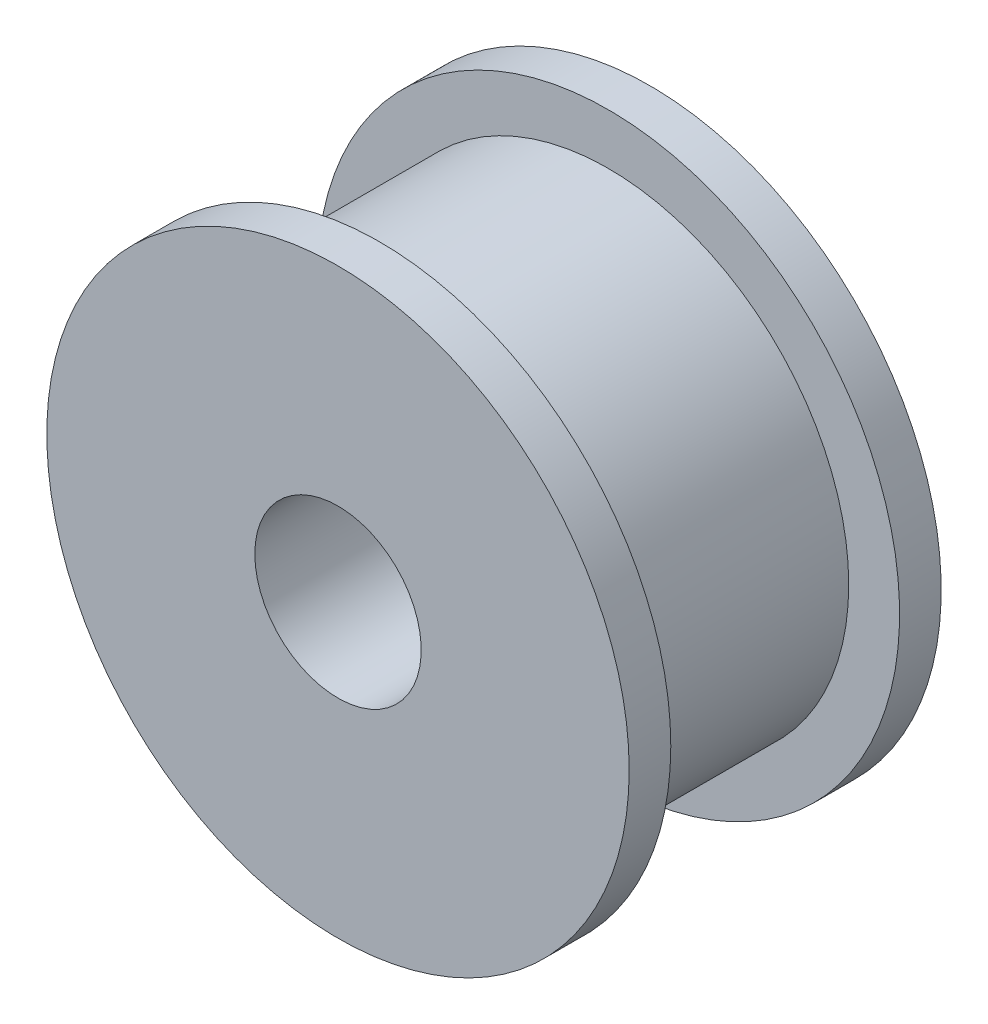
SolidWorks part; units mm, degrees
ref_plane "前视基准面" through (0, 0, 0) normal (0, 0, 1) x (1, 0, 0)
ref_plane "上视基准面" through (0, 0, 0) normal (0, 1, 0) x (1, 0, 0)
ref_plane "右视基准面" through (0, 0, 0) normal (1, 0, 0) x (0, 0, -1)
other "Configuration Table"
sketch "草图1" plane through (0, 0, 0) normal (0, 0, 1) x (1, 0, 0)
  circle A0 centre (0, 0) radius 11.555
  dimension "D1" = 23.11
extrude "凸台-拉伸1" add sketch "草图1" along normal blind 11
sketch "草图2" plane through (0, 0, 11) normal (0, 0, 1) x (1, 0, 0)
  circle A0 centre (0, 0) radius 14
  dimension "D1" = 28
extrude "凸台-拉伸2" add sketch "草图2" along normal blind 2
sketch "草图3" plane through (0, 0, 0) normal (0, 0, -1) x (-1, 0, 0)
  circle A1 centre (0, 0) radius 14 construction
  circle A2 centre (0, 0) radius 14
extrude "凸台-拉伸3" add sketch "草图3" along normal blind 2
sketch "草图4" plane through (0, 0, -2) normal (0, 0, -1) x (-1, 0, 0)
  circle A0 centre (0, 0) radius 4
  dimension "D1" = 8
extrude "切除-拉伸1" cut sketch "草图4" against normal through all
